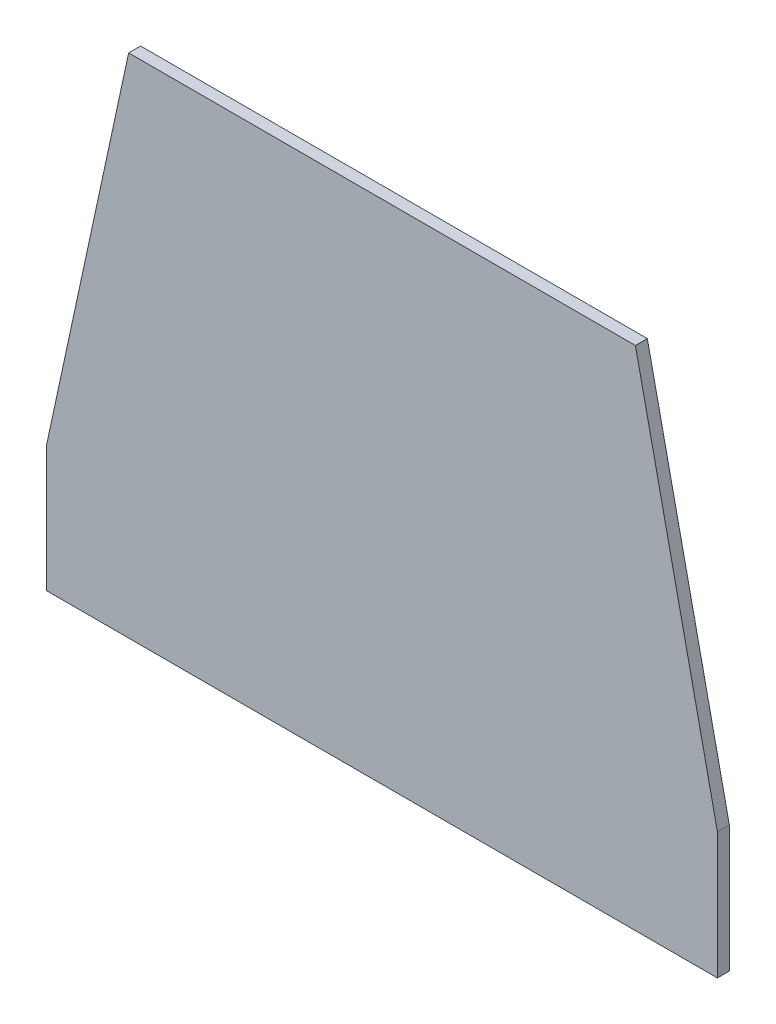
SolidWorks part; units mm, degrees
ref_plane "前视" through (0, 0, 0) normal (0, 0, 1) x (1, 0, 0)
ref_plane "上视" through (0, 0, 0) normal (0, 1, 0) x (1, 0, 0)
ref_plane "右视" through (0, 0, 0) normal (1, 0, 0) x (0, 0, -1)
sketch "草图2" plane through (0, 0, 0) normal (0, 0, 1) x (1, 0, 0)
  line L0 (110, 680) -> (0, 170)
  line L1 (0, 0) -> (900, 0)
  line L2 (0, 0) -> (0, 170)
  line L3 (110, 680) -> (790, 680)
  line L4 (900, 0) -> (900, 170)
  line L5 (450, 732.4608) -> (450, -110.1257) construction
  line L6 (790, 680) -> (900, 170)
  line L7 (110, 610) -> (938.0099, 610) construction
  line L8 (750, 870.5709) -> (750, 471.9627) construction
  line L9 (110, 310) -> (910, 310) construction
  line L10 (110, 530) -> (938.0099, 530) construction
  line L11 (450, 530) -> (944.1948, -87.8821) construction
  line L12 (603.3949, 164.813) -> (806.4775, 327.2426) construction
  line L13 (663.7287, 110.6282) -> (891.7517, 293.0057) construction
  line L14 (711.6834, 46.5423) -> (936.4569, 226.3208) construction
  line L15 (610.0301, 201.8375) -> (761.264, 12.7528) construction
  line L16 (733.9352, 303.0814) -> (876.4232, 124.9314) construction
  line L17 (506, 262.1445) -> (506, 27.5399) construction
  circle A0 centre (450, 50) radius 13
  circle A1 centre (450, 130) radius 13
  circle A2 centre (450, 210) radius 13
  circle A3 centre (837.8826, 45.038) radius 13
  circle A4 centre (62.1174, 45.038) radius 13
  circle A5 centre (506, 210) radius 13
  circle A6 centre (506, 130) radius 13
  circle A7 centre (506, 50) radius 13
  circle A8 centre (394, 50) radius 13
  circle A9 centre (394, 130) radius 13
  circle A10 centre (394, 210) radius 13
  circle A11 centre (510, 310) radius 13
  circle A12 centre (590, 310) radius 13
  circle A13 centre (310, 310) radius 13
  circle A14 centre (390, 310) radius 13
  circle A15 centre (750.4512, 282.4317) radius 13
  circle A16 centre (687.9763, 232.4629) radius 13
  circle A17 centre (800.42, 219.9567) radius 13
  circle A18 centre (850.3888, 157.4818) radius 13
  circle A19 centre (787.9138, 107.513) radius 13
  circle A20 centre (737.945, 169.988) radius 13
  circle A21 centre (725.4388, 57.5442) radius 13
  circle A22 centre (675.4701, 120.0192) radius 13
  circle A23 centre (625.5013, 182.4942) radius 13
  circle A24 centre (274.4987, 182.4942) radius 13
  circle A25 centre (224.5299, 120.0192) radius 13
  circle A26 centre (174.5612, 57.5442) radius 13
  circle A27 centre (162.055, 169.988) radius 13
  circle A28 centre (112.0862, 107.513) radius 13
  circle A29 centre (49.6112, 157.4818) radius 13
  circle A30 centre (99.58, 219.9567) radius 13
  circle A31 centre (212.0237, 232.4629) radius 13
  circle A32 centre (149.5488, 282.4317) radius 13
  point P5 (0, 170)
  point P6 (110, 680)
  point P15 (450, 50)
  dimension "D7" = 50
  dimension "D8" = 26
  dimension "D15" = 26
  dimension "D21" = 26
  dimension "D28" = 26
  dimension "D1" = 900
  dimension "D2" = 680
  dimension "D3" = 170
  dimension "D4" = 110
  dimension "D5" = 70
  dimension "D6" = 40
  dimension "D9" = 80
  dimension "D10" = 80
  dimension "D11" = 80
  dimension "D12" = 56
  dimension "D13" = 80
  dimension "D14" = 300
  dimension "D16" = 60
  dimension "D17" = 80
  dimension "D18" = 80
  dimension "D19" = 38.654
  dimension "D20" = 381
  dimension "D22" = 80
  dimension "D23" = 80
  dimension "D24" = 80
  dimension "D25" = 80
  dimension "D26" = 80
  dimension "D27" = 50
extrude "基体-拉伸" add sketch "草图2" along normal blind 16
sketch "草图3" plane through (0, 0, 16) normal (0, 0, 1) x (1, 0, 0)
  circle A0 centre (750, 610) radius 13
  dimension "D1" = 26
  dimension "D2" = 40
  dimension "D3" = 70
extrude "切除-拉伸1" cut sketch "草图3" against normal through all
pattern_linear "阵列(线性)1" count 4 spacing 80 along (-1, 0, 0) count 3 spacing 80 along (0, -1, 0) of "切除-拉伸1"
pattern_linear "阵列(线性)2" count 2 spacing 360 along (-1, 0, 0) of "阵列(线性)1", "切除-拉伸1"
sketch "草图4" plane through (0, 0, 16) normal (0, 0, 1) x (1, 0, 0)
  line L0 (110, 680) -> (790, 680)
  line L1 (790, 680) -> (900, 170)
  line L2 (900, 170) -> (900, 0)
  line L3 (900, 0) -> (0, 0)
  line L4 (0, 0) -> (0, 170)
  line L5 (0, 170) -> (110, 680)
extrude "凸台-拉伸1" add sketch "草图4" against normal blind 16
